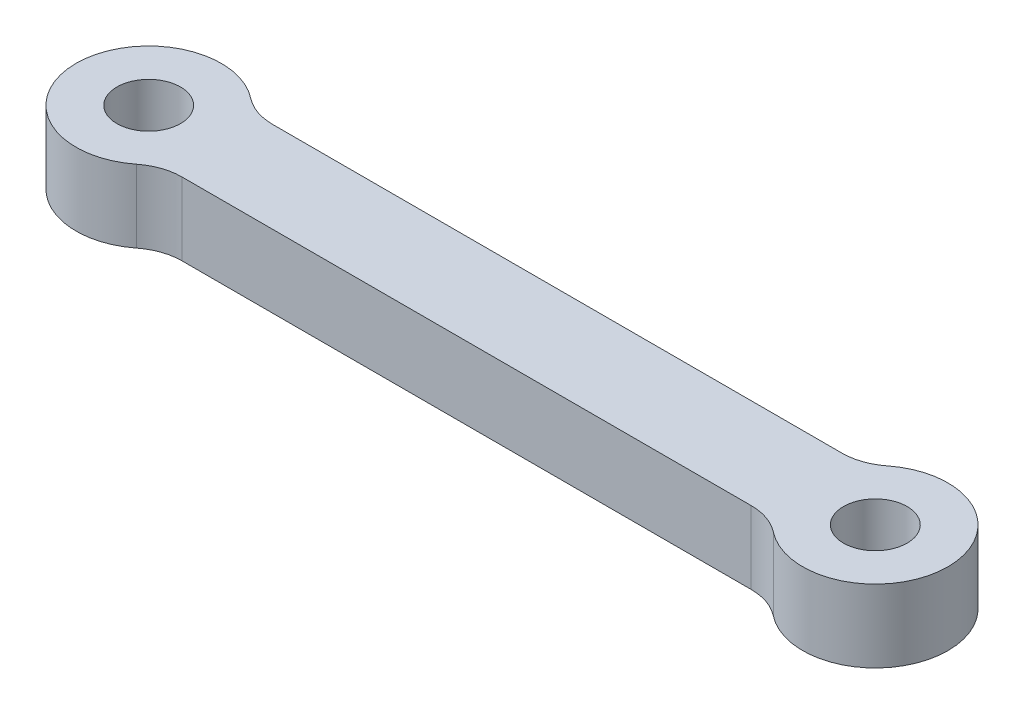
SolidWorks part; units mm, degrees
ref_plane "Front Plane" through (0, 0, 0) normal (0, 0, 1) x (1, 0, 0)
ref_plane "Top Plane" through (0, 0, 0) normal (0, 1, 0) x (1, 0, 0)
ref_plane "Right Plane" through (0, 0, 0) normal (1, 0, 0) x (0, 0, -1)
sketch "Sketch1" plane through (0, 0, 0) normal (0, 1, 0) x (1, 0, 0)
  line L0 (0, 0) -> (40, 0) construction
  line L1 (3.1225, 2.5) -> (36.8775, 2.5)
  line L2 (3.1225, -2.5) -> (36.8775, -2.5)
  circle A0 centre (0, 0) radius 4
  circle A1 centre (40, 0) radius 4
  circle A2 centre (0, 0) radius 1.75
  circle A3 centre (40, 0) radius 1.75
  dimension "D1" = 8
  dimension "D3" = 8
  dimension "D5" = 3.5
  dimension "D6" = 3.5
  dimension "D2" = 40
  dimension "D4" = 2.5
extrude "Boss-Extrude1" add sketch "Sketch1" along normal blind 4
fillet "Fillet1" radius 3 4 edges at (3.1225, 2, 2.5) (36.8775, 2, 2.5) (36.8775, 2, -2.5) (3.1225, 2, -2.5)
